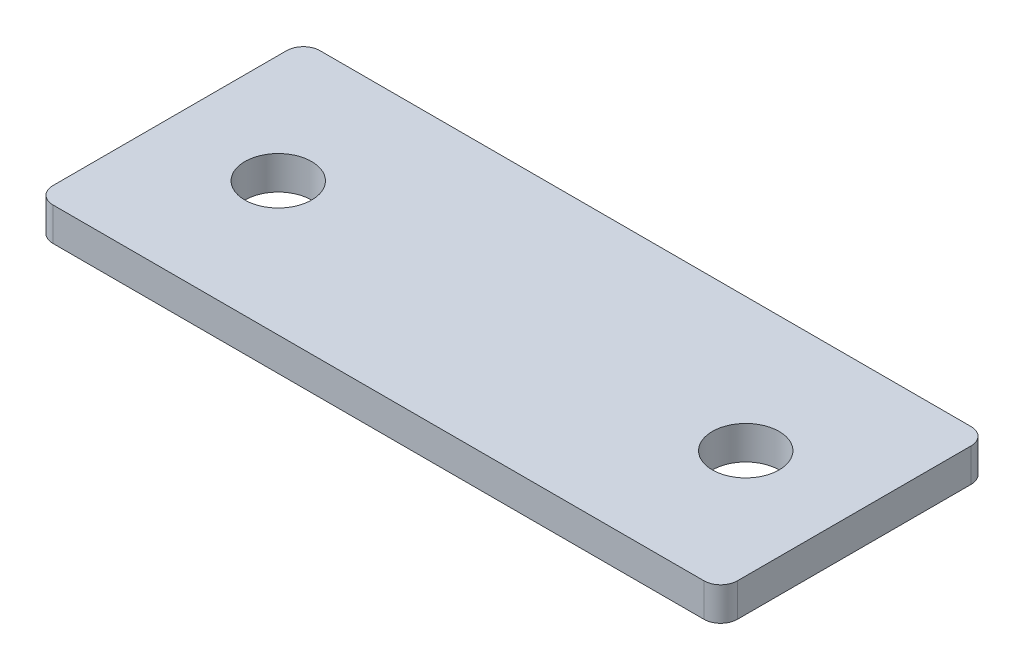
SolidWorks part; units mm, degrees
ref_plane "前视基准面" through (0, 0, 0) normal (0, 0, 1) x (1, 0, 0)
ref_plane "上视基准面" through (0, 0, 0) normal (0, 1, 0) x (1, 0, 0)
ref_plane "右视基准面" through (0, 0, 0) normal (1, 0, 0) x (0, 0, -1)
sketch "草图1" plane through (0, 0, 0) normal (0, 1, 0) x (1, 0, 0)
  line L0 (-20.5, 0) -> (20.5, 0) construction
  line L1 (-20.5, 8) -> (20.5, 8)
  line L2 (-20.5, 8) -> (-20.5, -8)
  line L3 (-20.5, -8) -> (20.5, -8)
  line L4 (20.5, 8) -> (20.5, -8)
  line L5 (-20.5, 8) -> (20.5, -8) construction
  line L6 (-20.5, -8) -> (20.5, 8) construction
  line L7 (0, 8) -> (0, -8) construction
  circle A0 centre (-14, 0) radius 2
  circle A1 centre (14, 0) radius 2
  point P0 (0, 0)
  dimension "D3" = 28
  dimension "D1" = 41
  dimension "D2" = 16
extrude "凸台-拉伸1" add sketch "草图1" along normal blind 2
fillet "圆角1" radius 1 1 edges at (20.5, 1, 8)
fillet "圆角2" radius 1 1 edges at (-20.5, 1, 8)
fillet "圆角3" radius 1 1 edges at (-20.5, 1, -8)
fillet "圆角4" radius 1 1 edges at (20.5, 1, -8)
